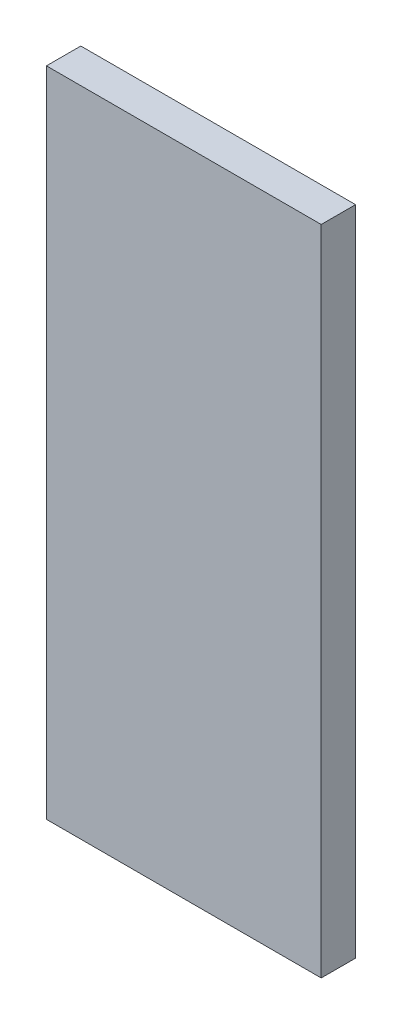
SolidWorks part; units mm, degrees
ref_plane "Front Plane" through (0, 0, 0) normal (0, 0, 1) x (1, 0, 0)
ref_plane "Top Plane" through (0, 0, 0) normal (0, 1, 0) x (1, 0, 0)
ref_plane "Right Plane" through (0, 0, 0) normal (1, 0, 0) x (0, 0, -1)
sketch "Sketch1" plane through (0, 0, 0) normal (0, 0, 1) x (1, 0, 0)
  line L1 (0, 0) -> (25.4, 0)
  line L2 (0, 0) -> (0, -60.325)
  line L3 (0, -60.325) -> (25.4, -60.325)
  line L4 (25.4, 0) -> (25.4, -60.325)
  dimension "D1" = 60.325
  dimension "D2" = 25.4
extrude "Boss-Extrude1" add sketch "Sketch1" along normal blind 3.175
